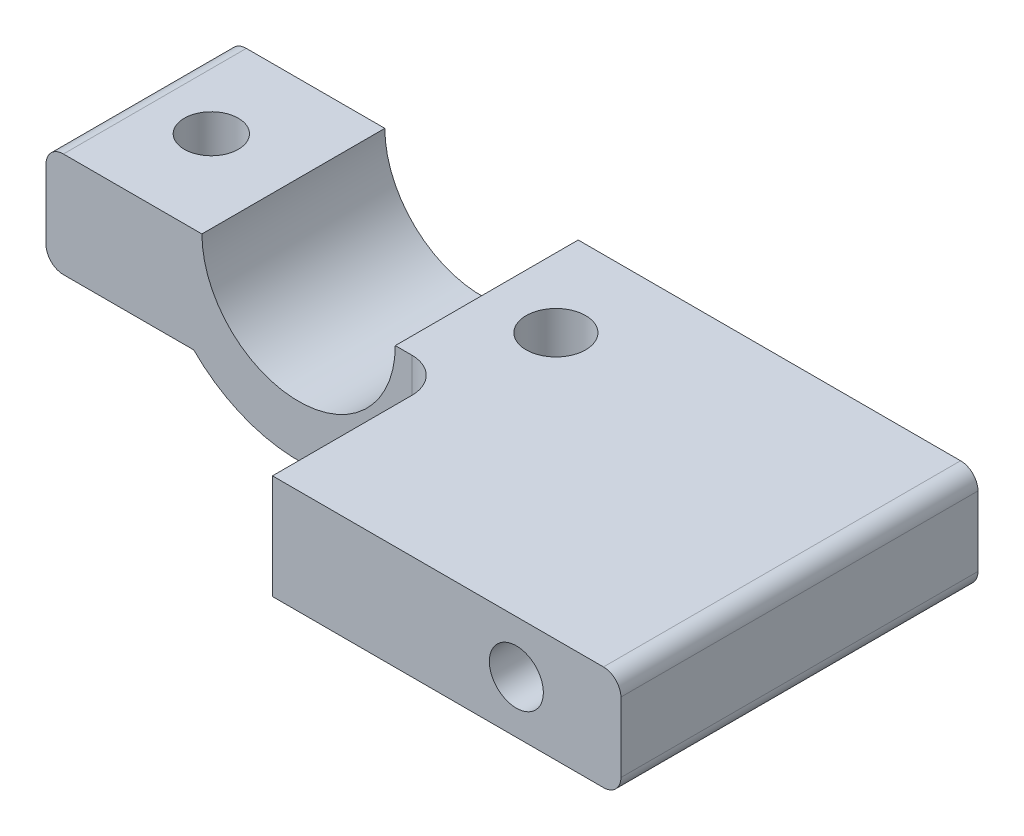
SolidWorks part; units mm, degrees
ref_plane "前视基准面" through (0, 0, 0) normal (0, 0, 1) x (1, 0, 0)
ref_plane "上视基准面" through (0, 0, 0) normal (0, 1, 0) x (1, 0, 0)
ref_plane "右视基准面" through (0, 0, 0) normal (1, 0, 0) x (0, 0, -1)
other "Configuration Table"
sketch "草图1" plane through (0, 0, 0) normal (0, 0, 1) x (1, 0, 0)
  line L1 (-8.5, 0) -> (-5.55, 0)
  line L2 (-8.5, 0) -> (-14.5, 0)
  line L3 (-14.5, 0) -> (-14.5, -6)
  line L4 (-14.5, -6) -> (-6.0208, -6)
  line L5 (8.5, 0) -> (28.5, 0)
  line L6 (28.5, 0) -> (28.5, -6)
  line L7 (28.5, -6) -> (6.0208, -6)
  line L8 (5.55, 0) -> (8.5, 0)
  arc A0 (-5.55, 0) -> (5.55, 0) centre (0, 0) ccw
  arc A1 (-8.5, 0) -> (8.5, 0) centre (0, 0) ccw
  dimension "D1" = 11.1
  dimension "D2" = 17
  dimension "D3" = 6
  dimension "D4" = 6
  dimension "D5" = 20
  dimension "D6" = 6
extrude "凸台-拉伸1" add sketch "草图1" along normal blind 10.5 contours A1 L2 L3 L4 | L1 A1 L8 A0 | A1 L7 L6 L5
sketch "草图2" plane through (0, -6, 0) normal (0, -1, 0) x (1, 0, 0)
  line L0 (-6.0208, 10.5) -> (-14.5, 0) construction
  circle A0 centre (-10.2604, 5.25) radius 1.55
  dimension "D1" = 3.1
extrude "切除-拉伸1" cut sketch "草图2" against normal through all
sketch "草图3" plane through (0, -6, 0) normal (0, -1, 0) x (1, 0, 0)
  line L0 (6.0208, 5.25) -> (9.5208, 5.25) construction
  line L1 (6.0208, 10.5) -> (6.0208, 0) construction
  circle A0 centre (9.5208, 5.25) radius 1.7073
  dimension "D1" = 3.5
extrude "切除-拉伸2" cut sketch "草图3" against normal through all
sketch "草图5" plane through (0, 0, 10.5) normal (0, 0, 1) x (1, 0, 0)
  line L0 (5.55, 0) -> (28.5, 0) construction
  line L1 (28.5, -6) -> (8.5, -6)
  line L2 (28.5, -6) -> (28.5, 0)
  line L3 (28.5, 0) -> (8.5, 0)
  line L4 (8.5, -6) -> (8.5, 0)
  dimension "D1" = 20
extrude "凸台-拉伸2" add sketch "草图5" along normal blind 10
sketch "草图6" plane through (0, 0, 20.5) normal (0, 0, 1) x (1, 0, 0)
  circle A0 centre (22.5, -3) radius 1.55
extrude "切除-拉伸4" cut sketch "草图6" against normal blind 10
fillet "圆角1" radius 2 1 edges at (8.5, -3, 10.5)
fillet "圆角2" radius 1 4 edges at (28.5, 0, 10.25) (28.5, -6, 10.25) (-14.5, -6, 5.25) (-14.5, 0, 5.25)
